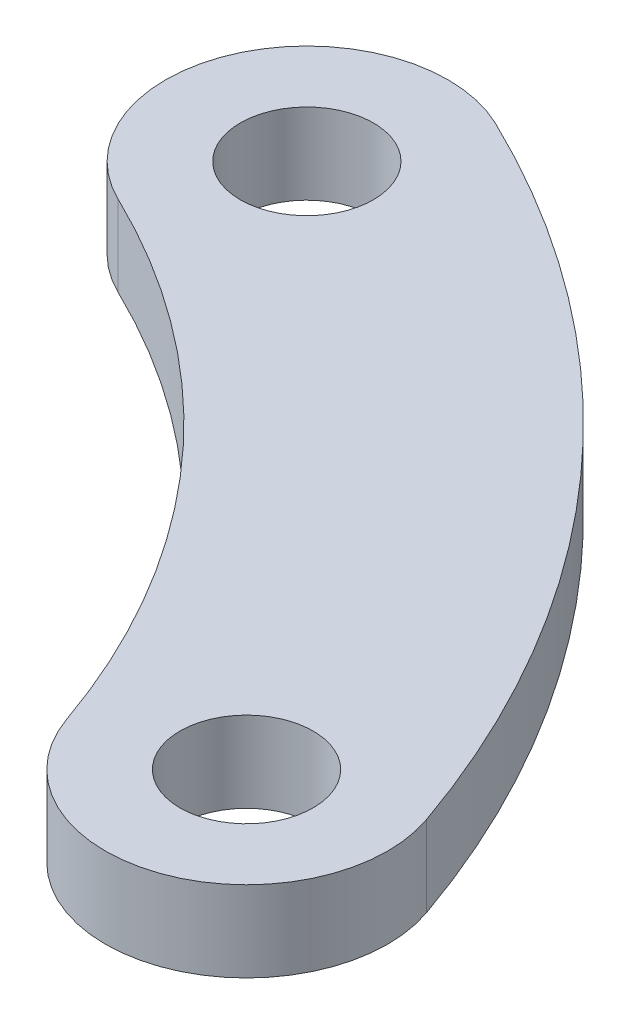
SolidWorks part; units mm, degrees
ref_plane "Front Plane" through (0, 0, 0) normal (0, 0, 1) x (1, 0, 0)
ref_plane "Top Plane" through (0, 0, 0) normal (0, 1, 0) x (1, 0, 0)
ref_plane "Right Plane" through (0, 0, 0) normal (1, 0, 0) x (0, 0, -1)
sketch "Sketch1" plane through (0, 2, 0) normal (0, 1, 0) x (1, 0, 0)
  line L0 (0, 0) -> (22.8034, 7.9515) construction
  line L1 (0, 0) -> (10.5019, 21.747) construction
  circle A10 centre (0, 0) radius 24.15 construction
  arc A12 (10.5019, 21.747) -> (22.8034, 7.9515) centre (0, 0) cw construction
  arc A13 (26.1083, 9.1038) -> (12.024, 24.8987) centre (0, 0) ccw
  arc A14 (19.4986, 6.7991) -> (8.9799, 18.5953) centre (0, 0) ccw
  arc A15 (19.4986, 6.7991) -> (26.1083, 9.1038) centre (22.8034, 7.9515) ccw
  arc A16 (12.024, 24.8987) -> (8.9799, 18.5953) centre (10.5019, 21.747) ccw
  circle A17 centre (10.5019, 21.747) radius 1.65
  circle A18 centre (22.8034, 7.9515) radius 1.65
  point P16 (18.0247, 16.0727)
  dimension "D1" = 48.3
  dimension "D2" = 45
  dimension "D3" = 3.5
  dimension "D4" = 3.3
  dimension "D5" = 3.3
extrude "Boss-Extrude1" add sketch "Sketch1" along normal blind 2
